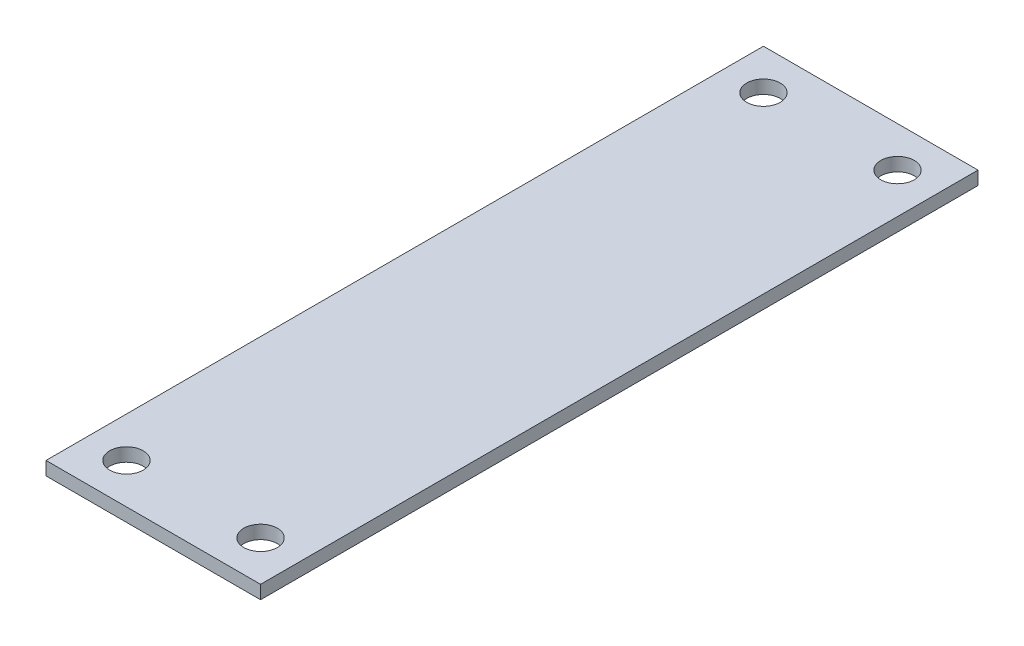
SolidWorks part; units mm, degrees
material "6061 合金"
ref_plane "前视基准面" through (0, 0, 0) normal (0, 0, 1) x (1, 0, 0)
ref_plane "上视基准面" through (0, 0, 0) normal (0, 1, 0) x (1, 0, 0)
ref_plane "右视基准面" through (0, 0, 0) normal (1, 0, 0) x (0, 0, -1)
sketch "草图1" plane through (0, 0, 0) normal (0, 1, 0) x (1, 0, 0)
  line L4 (-16.1581, 92.7664) -> (-16.1581, -14.2336)
  line L5 (15.8419, 92.7664) -> (15.8419, -14.2336)
  line L7 (-16.1581, 92.7664) -> (15.8419, 92.7664)
  line L8 (-16.1581, -14.2336) -> (15.8419, -14.2336)
  circle A0 centre (-10.1581, 86.7664) radius 2.5
  circle A1 centre (9.8419, 86.7664) radius 2.5
  circle A2 centre (-10.1581, -8.2336) radius 2.5
  circle A3 centre (9.8419, -8.2336) radius 2.5
extrude "凸台-拉伸1" add sketch "草图1" along normal blind 2
